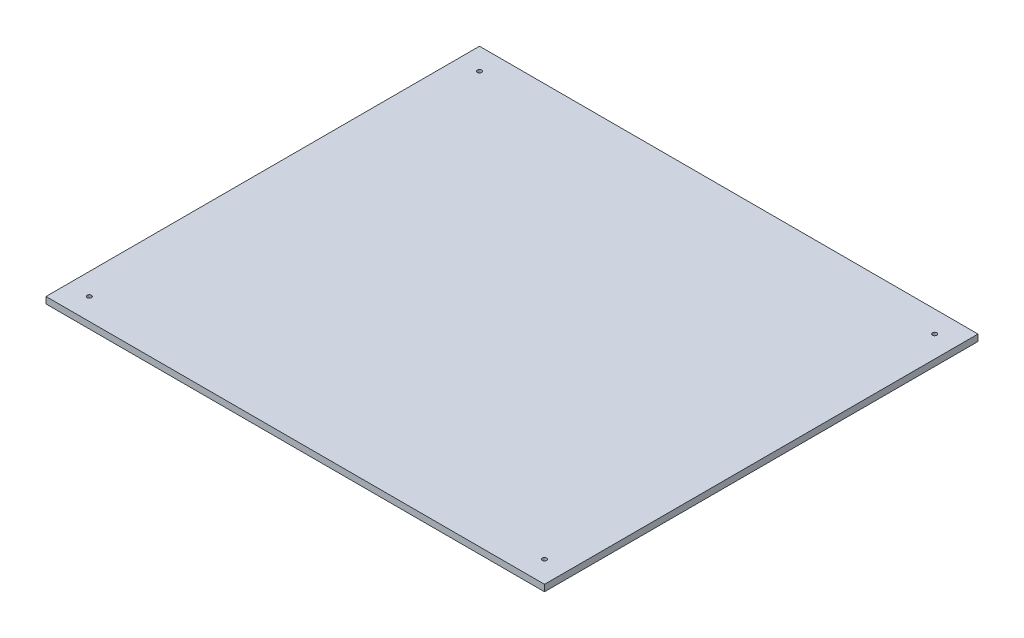
SolidWorks part; units mm, degrees
ref_plane "Front Plane" through (0, 0, 0) normal (0, 0, 1) x (1, 0, 0)
ref_plane "Top Plane" through (0, 0, 0) normal (0, 1, 0) x (1, 0, 0)
ref_plane "Right Plane" through (0, 0, 0) normal (1, 0, 0) x (0, 0, -1)
sketch "Sketch1" plane through (0, 0, 0) normal (0, 1, 0) x (1, 0, 0)
  line L0 (0, 0) -> (0, 180.5285) construction
  line L1 (0, 0) -> (61.9422, 0) construction
  line L2 (-115, 90) -> (-105, 90) construction
  line L7 (-105, 90) -> (-105, 100) construction
  line L8 (105, 90) -> (105, 100) construction
  line L9 (115, 90) -> (105, 90) construction
  line L10 (115, -90) -> (105, -90) construction
  line L11 (105, -90) -> (105, -100) construction
  line L12 (-105, -90) -> (-105, -100) construction
  line L13 (-115, -90) -> (-105, -90) construction
  line L15 (-115, 100) -> (115, 100)
  line L16 (-115, 100) -> (-115, -100)
  line L17 (-115, -100) -> (115, -100)
  line L18 (115, 100) -> (115, -100)
  circle A16 centre (-105, 90) radius 1
  circle A17 centre (105, 90) radius 1
  circle A20 centre (105, -90) radius 1
  circle A21 centre (-105, -90) radius 1
  dimension "D5" = 2
  dimension "D3" = 10
  dimension "D4" = 10
  dimension "D1" = 230
  dimension "D2" = 200
extrude "Boss-Extrude1" add sketch "Sketch1" along normal blind 3
equation "\"Base thickness\"= 3mm"
equation "\"Base attach hole diameter\"= 2mm"
equation "\"D1@Boss-Extrude1\"=\"Base thickness\""
equation "\"D5@Sketch1\"=\"Base attach hole diameter\""
